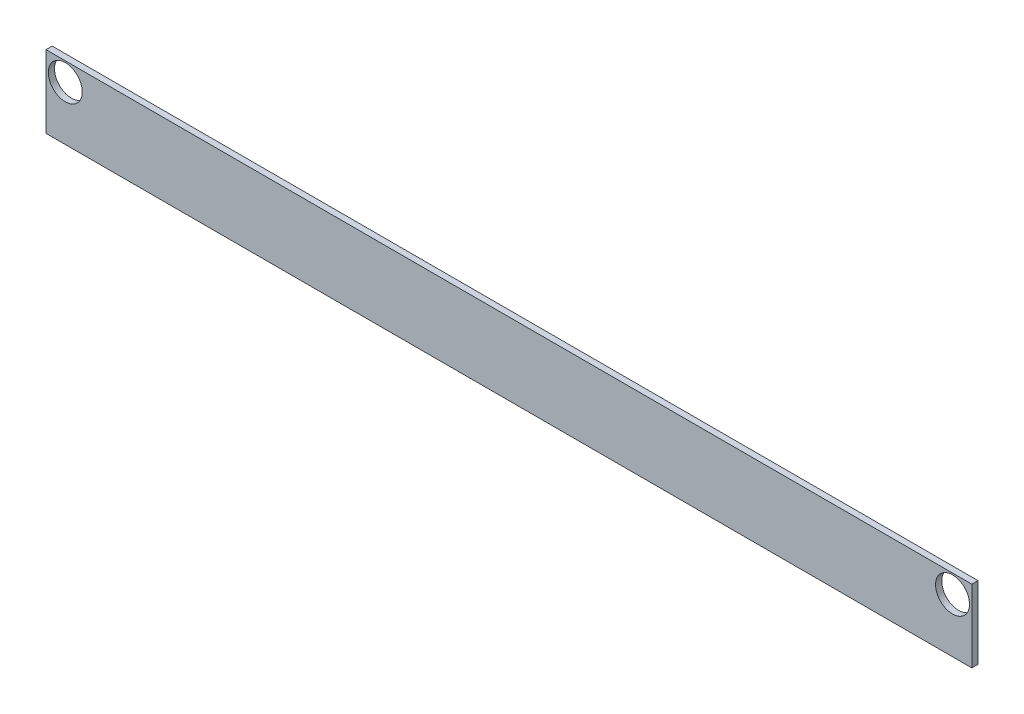
SolidWorks part; units mm, degrees
ref_plane "Alzado" through (0, 0, 0) normal (0, 0, 1) x (1, 0, 0)
ref_plane "Planta" through (0, 0, 0) normal (0, 1, 0) x (1, 0, 0)
ref_plane "Vista lateral" through (0, 0, 0) normal (1, 0, 0) x (0, 0, -1)
sketch "Croquis1" plane through (0, 0, 0) normal (0, 0, 1) x (1, 0, 0)
  line L1 (-300, -35) -> (300, -35)
  line L2 (-300, -35) -> (-300, 12)
  line L3 (-300, 12) -> (300, 12)
  line L4 (300, -35) -> (300, 12)
  point P0 (0, 0)
  point P7 (0, 12)
  dimension "D1" = 600
  dimension "D2" = 35
  dimension "D3" = 12
extrude "Saliente-Extruir1" add sketch "Croquis1" along normal blind 4
sketch "Croquis2" plane through (0, 0, 4) normal (0, 0, 1) x (1, 0, 0)
  line L0 (0, 77.1493) -> (0, -84.3512) construction
  circle A0 centre (287.5, 0) radius 11
  circle A2 centre (-287.5, 0) radius 11
  dimension "D2" = 22
  dimension "D1" = 287.5
extrude "Cortar-Extruir1" cut sketch "Croquis2" against normal blind 4
